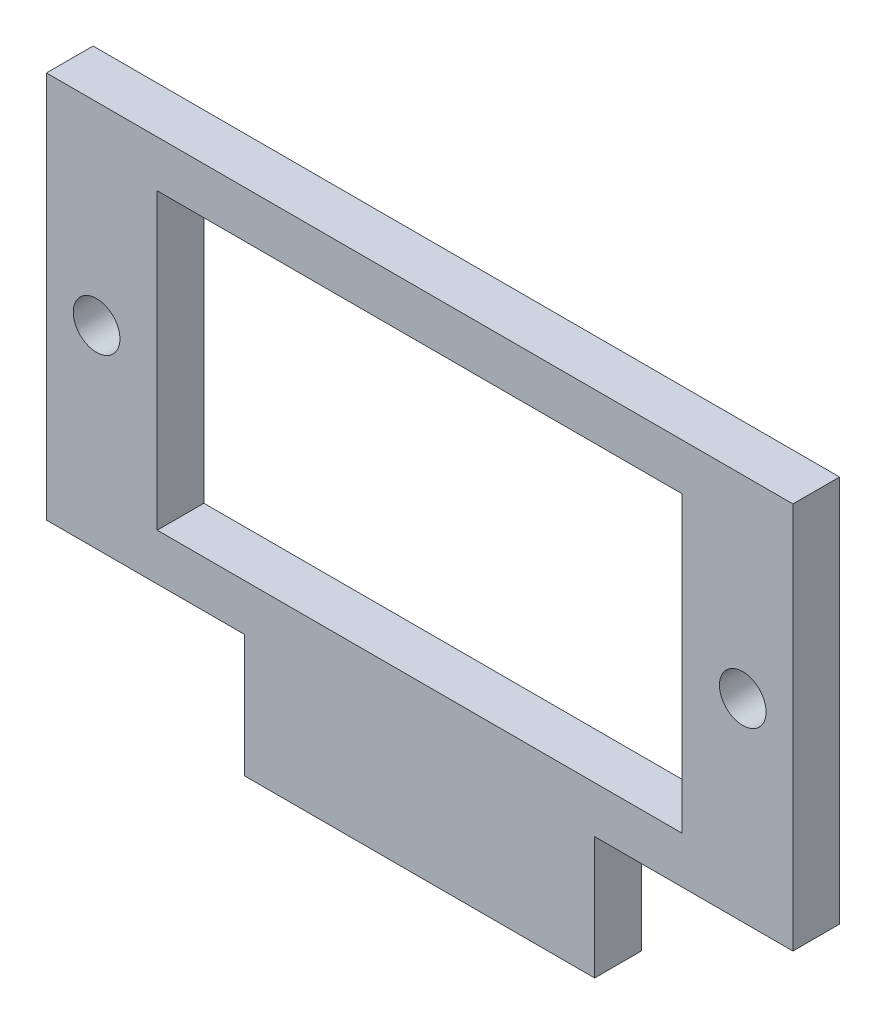
SolidWorks part; units mm, degrees
ref_plane "Front Plane" through (0, 0, 0) normal (0, 0, 1) x (1, 0, 0)
ref_plane "Top Plane" through (0, 0, 0) normal (0, 1, 0) x (1, 0, 0)
ref_plane "Right Plane" through (0, 0, 0) normal (1, 0, 0) x (0, 0, -1)
sketch "Sketch1" plane through (0, 0, 0) normal (0, 0, 1) x (1, 0, 0)
  line L1 (-11.25, 6.3) -> (11.25, 6.3)
  line L2 (-11.25, 6.3) -> (-11.25, -6.3)
  line L3 (-11.25, -6.3) -> (11.25, -6.3)
  line L4 (11.25, 6.3) -> (11.25, -6.3)
  line L5 (-11.25, 6.3) -> (11.25, -6.3) construction
  line L6 (-11.25, -6.3) -> (11.25, 6.3) construction
  line L10 (-21.7361, 0) -> (22.0139, 0) construction
  line L11 (-16, 8.3) -> (16, 8.3)
  line L12 (-16, 8.3) -> (-16, -8.3)
  line L13 (-16, -8.3) -> (16, -8.3)
  line L14 (16, 8.3) -> (16, -8.3)
  line L15 (-16, 8.3) -> (16, -8.3) construction
  line L16 (-16, -8.3) -> (16, 8.3) construction
  line L17 (0, 9.4697) -> (0, -11.1366) construction
  circle A0 centre (-13.85, 0) radius 1
  circle A1 centre (13.85, 0) radius 1
  point P0 (0, 0)
  point P6 (0, 0)
  point P17 (0, 0)
  dimension "D5" = 2
  dimension "D6" = 2
  dimension "D1" = 22.5
  dimension "D2" = 12.6
  dimension "D4" = 2
  dimension "D3" = 32
  dimension "D7" = 27.7
extrude "Boss-Extrude1" add sketch "Sketch1" along normal blind 2
sketch "Sketch2" plane through (0, -8.3, 0) normal (0, -1, 0) x (1, 0, 0)
  line L0 (-16, 2) -> (16, 2) construction
  line L1 (-7.5, 2) -> (7.5, 2)
  line L2 (-7.5, 2) -> (-7.5, 0)
  line L3 (-7.5, 0) -> (7.5, 0)
  line L4 (7.5, 2) -> (7.5, 0)
  line L5 (-16, 0) -> (16, 0) construction
  line L6 (0, 3.7698) -> (0, -2.1928) construction
  dimension "D1" = 15
extrude "Boss-Extrude2" add sketch "Sketch2" along normal blind 5.25
